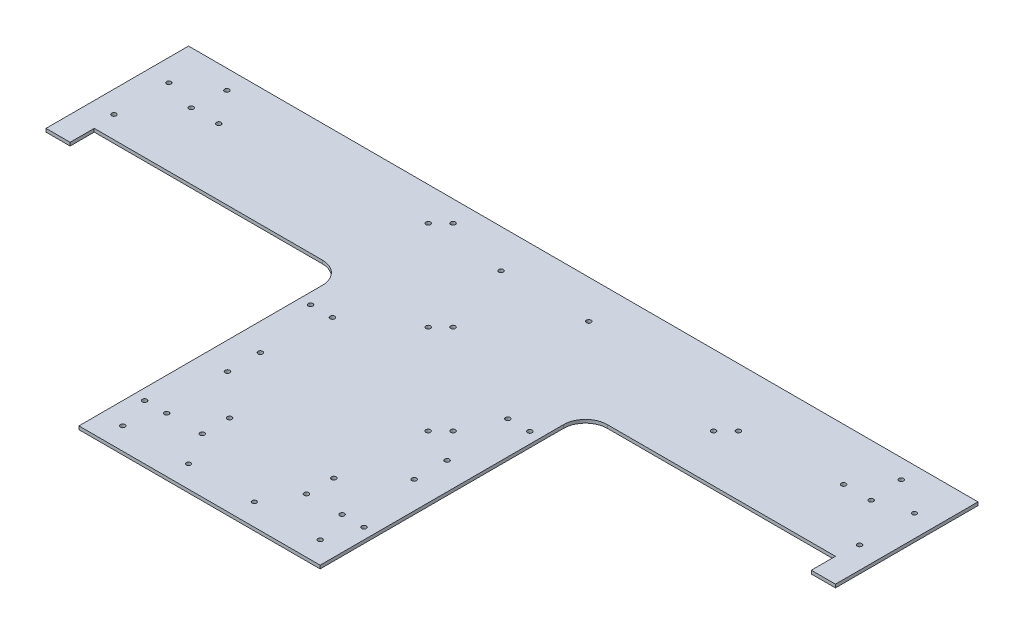
SolidWorks part; units mm, degrees
ref_plane "Front Plane" through (0, 0, 0) normal (0, 0, 1) x (1, 0, 0)
ref_plane "Top Plane" through (0, 0, 0) normal (0, 1, 0) x (1, 0, 0)
ref_plane "Right Plane" through (0, 0, 0) normal (1, 0, 0) x (0, 0, -1)
sketch "Sketch1" plane through (0, 0, 0) normal (0, 1, 0) x (1, 0, 0)
  line L0 (-110, 350) -> (-110, 108)
  line L1 (-110, 108) -> (-338, 108)
  line L2 (-338, 108) -> (-338, 130)
  line L3 (-338, 130) -> (-360, 130)
  line L4 (-360, 130) -> (-360, -130)
  line L5 (-360, 0) -> (1003.1457, 0) construction
  line L6 (0, 350) -> (0, -620.7989) construction
  line L7 (-338, -130) -> (-360, -130)
  line L8 (-338, -108) -> (-338, -130)
  line L9 (-110, -108) -> (-338, -108)
  line L10 (-110, 350) -> (110, 350)
  line L11 (-110, -350) -> (-110, -108)
  line L12 (-110, -350) -> (110, -350)
  line L13 (110, -350) -> (110, -108)
  line L14 (110, -108) -> (338, -108)
  line L15 (338, -108) -> (338, -130)
  line L16 (338, -130) -> (360, -130)
  line L17 (360, 130) -> (360, -130)
  line L18 (338, 130) -> (360, 130)
  line L19 (338, 108) -> (338, 130)
  line L20 (110, 108) -> (338, 108)
  line L21 (110, 350) -> (110, 108)
  point P17 (0, -350)
  dimension "D1" = 110
  dimension "D2" = 22
  dimension "D3" = 22
  dimension "D4" = 242
  dimension "D5" = 130
  dimension "D6" = 250
  dimension "D7" = 110
  dimension "D8" = 108
extrude "Boss-Extrude1" add sketch "Sketch1" along normal blind 3
sketch "Sketch2" plane through (0, 3, 0) normal (0, 1, 0) x (1, 0, 0)
  line L0 (360, -130) -> (360, 130) construction
  line L2 (338, 108) -> (110, 108) construction
  line L4 (0, 107.9437) -> (0, -458.275) construction
  line L5 (110, 108) -> (110, 350) construction
  line L6 (110, 350) -> (-110, 350) construction
  line L7 (-540.1841, 0) -> (-80.3508, 0) construction
  circle A0 centre (310, 47.5) radius 2.125
  circle A1 centre (285, 47.5) radius 2.125
  circle A2 centre (307.5, 17.5) radius 2.125
  circle A3 centre (307.5, -17.5) radius 2.125
  circle A4 centre (310, -47.5) radius 2.125
  circle A5 centre (285, -47.5) radius 2.125
  circle A6 centre (-285, -47.5) radius 2.125
  circle A7 centre (-310, -47.5) radius 2.125
  circle A8 centre (-307.5, -17.5) radius 2.125
  circle A9 centre (-307.5, 17.5) radius 2.125
  circle A10 centre (-285, 47.5) radius 2.125
  circle A11 centre (-310, 47.5) radius 2.125
  circle A13 centre (47.5, 300) radius 2.125
  circle A15 centre (47.5, 275) radius 2.125
  circle A16 centre (-47.5, 275) radius 2.125
  circle A17 centre (-47.5, 300) radius 2.125
  circle A18 centre (-47.5, -300) radius 2.125
  circle A19 centre (-47.5, -275) radius 2.125
  circle A20 centre (47.5, -275) radius 2.125
  circle A21 centre (47.5, -300) radius 2.125
  dimension "D1" = 4.25
  dimension "D2" = 4.25
  dimension "D3" = 4.25
  dimension "D4" = 4.25
  dimension "D5" = 4.25
  dimension "D6" = 4.25
  dimension "D15" = 4.25
  dimension "D16" = 4.25
  dimension "D7" = 50
  dimension "D8" = 25
  dimension "D9" = 95
  dimension "D10" = 35
  dimension "D11" = 60.5
  dimension "D12" = 90.5
  dimension "D13" = 52.5
  dimension "D14" = 110
  dimension "D17" = 50
  dimension "D18" = 25
  dimension "D19" = 62.5
  dimension "D20" = 108
extrude "Cut-Extrude1" cut sketch "Sketch2" against normal through all
sketch "Sketch3" plane through (0, 3, 0) normal (0, 1, 0) x (1, 0, 0)
  line L0 (360, -130) -> (360, 130) construction
  line L1 (338, 108) -> (110, 108) construction
  line L2 (-553.4456, 0) -> (-91.4299, 0) construction
  line L3 (0, 286.895) -> (0, -255.8046) construction
  line L4 (110, 108) -> (110, 350) construction
  line L5 (110, 350) -> (-110, 350) construction
  line L6 (-110, 350) -> (-110, 108) construction
  circle A0 centre (340, 38) radius 2
  circle A2 centre (340, -38) radius 2
  circle A3 centre (-340, -38) radius 2
  circle A4 centre (-340, 38) radius 2
  circle A5 centre (-30, 330) radius 2
  circle A7 centre (30, 330) radius 2
  circle A8 centre (30, -330) radius 2
  circle A9 centre (-30, -330) radius 2
  dimension "D1" = 4
  dimension "D6" = 4
  dimension "D7" = 80
  dimension "D2" = 20
  dimension "D3" = 70
  dimension "D4" = 108
  dimension "D5" = 110
  dimension "D8" = 20
extrude "Cut-Extrude2" cut sketch "Sketch3" against normal through all
sketch "Sketch5" plane through (0, 3, 0) normal (0, 1, 0) x (1, 0, 0)
  line L0 (110, 350) -> (-110, 350) construction
  line L1 (110, 108) -> (110, 350) construction
  line L2 (0, 224.365) -> (185.6725, 224.365) construction
  line L3 (90, 361.0488) -> (90, 126.2188) construction
  line L4 (0, 375.894) -> (0, 88.4107) construction
  line L5 (349.7475, 0) -> (-242.2654, 0) construction
  circle A0 centre (80, 300) radius 2.125
  circle A1 centre (80, 148.73) radius 2.125
  circle A2 centre (85.11, 239.365) radius 2.125
  circle A3 centre (85.11, 209.365) radius 2.125
  circle A4 centre (100, 148.73) radius 2.125
  circle A5 centre (100, 300) radius 2.125
  circle A6 centre (-100, 300) radius 2.125
  circle A7 centre (-100, 148.73) radius 2.125
  circle A8 centre (-85.11, 209.365) radius 2.125
  circle A9 centre (-85.11, 239.365) radius 2.125
  circle A10 centre (-80, 148.73) radius 2.125
  circle A11 centre (-80, 300) radius 2.125
  circle A12 centre (-80, -300) radius 2.125
  circle A13 centre (-80, -148.73) radius 2.125
  circle A14 centre (-85.11, -239.365) radius 2.125
  circle A15 centre (-85.11, -209.365) radius 2.125
  circle A16 centre (-100, -148.73) radius 2.125
  circle A17 centre (-100, -300) radius 2.125
  circle A18 centre (100, -300) radius 2.125
  circle A19 centre (100, -148.73) radius 2.125
  circle A20 centre (85.11, -209.365) radius 2.125
  circle A21 centre (85.11, -239.365) radius 2.125
  circle A22 centre (80, -148.73) radius 2.125
  circle A23 centre (80, -300) radius 2.125
  dimension "D1" = 4.25
  dimension "D2" = 4.25
  dimension "D6" = 4.25
  dimension "D7" = 4.25
  dimension "D3" = 151.27
  dimension "D4" = 50
  dimension "30" = 30
  dimension "D5" = 5.11
  dimension "D8" = 30
  dimension "D9" = 75.635
  dimension "D10" = 15
  dimension "D11" = 10
extrude "Cut-Extrude4" cut sketch "Sketch5" against normal blind 10
fillet "Fillet1" radius 20 4 edges at (110, 1.5, -108) (-110, 1.5, -108) (-110, 1.5, 108) (110, 1.5, 108)
sketch "Sketch6" plane through (0, 3, 0) normal (0, 1, 0) x (1, 0, 0)
  line L0 (-327.256, 327.256) -> (0, 0) construction
  line L1 (0, 429.479) -> (0, -412.5125) construction
  line L2 (-249.4214, 108) -> (110, -251.4214) construction
  line L3 (-226.7939, 108) -> (110, -228.7939) construction
  line L4 (327.256, 327.256) -> (0, 0) construction
  line L5 (-244.4559, 114.3482) -> (114.8318, -244.9395) construction
  line L6 (-130, 108) -> (-338, 108) construction
  line L7 (110, -350) -> (110, -128) construction
  circle A0 centre (53.3259, -194.7473) radius 2.125
  circle A1 centre (-192.7473, 51.3259) radius 2.125
  circle A2 centre (-28.6985, -112.7229) radius 2.125
  circle A3 centre (-110.7229, -30.6985) radius 2.125
  circle A4 centre (64.6396, -183.4335) radius 2.125
  circle A5 centre (-17.3848, -101.4092) radius 2.125
  circle A6 centre (-99.4092, -19.3848) radius 2.125
  circle A7 centre (-181.4335, 62.6396) radius 2.125
  circle A8 centre (-62.6396, 181.4335) radius 2.125
  circle A9 centre (19.3848, 99.4092) radius 2.125
  circle A10 centre (101.4092, 17.3848) radius 2.125
  circle A11 centre (183.4335, -64.6396) radius 2.125
  circle A12 centre (30.6985, 110.7229) radius 2.125
  circle A13 centre (112.7229, 28.6985) radius 2.125
  circle A14 centre (-51.3259, 192.7473) radius 2.125
  circle A15 centre (194.7473, -53.3259) radius 2.125
  point P23 (-69.7107, -71.7107)
  point P49 (71.7107, 69.7107)
  dimension "D3" = 4.25
  dimension "D5" = 4.25
  dimension "D8" = 4.25
  dimension "D10" = 4.25
  dimension "D1" = 45
  dimension "D2" = 100
  dimension "D4" = 16
  dimension "D6" = 348
  dimension "D7" = 174
  dimension "D9" = 116
  dimension "D11" = 116
  dimension "D12" = 8
extrude "Cut-Extrude5" cut sketch "Sketch6" against normal through all
sketch "Sketch7" plane through (0, 3, 0) normal (0, 1, 0) x (1, 0, 0)
  line L0 (0, 227.3539) -> (0, -244.3347) construction
  line L1 (-222.6371, 0) -> (245.907, 0) construction
  line L2 (360, -130) -> (360, 130) construction
  line L3 (338, 108) -> (130, 108) construction
  line L4 (110, 350) -> (-110, 350) construction
  line L5 (-110, 350) -> (-110, 128) construction
  circle A0 centre (340, 88) radius 2.1
  circle A1 centre (340, -88) radius 2.1
  circle A2 centre (-340, -88) radius 2.1
  circle A3 centre (-340, 88) radius 2.1
  circle A4 centre (-90, 330) radius 2.1
  circle A5 centre (90, 330) radius 2.1
  circle A6 centre (90, -330) radius 2.1
  circle A7 centre (-90, -330) radius 2.1
  dimension "D1" = 4.2
  dimension "D2" = 20
  dimension "D3" = 20
  dimension "D4" = 4.2
  dimension "D5" = 20
  dimension "D6" = 20
sketch "Sketch8" plane through (0, 3, 0) normal (0, 1, 0) x (1, 0, 0)
  line L0 (0, 227.3539) -> (0, -244.3347) construction
  line L1 (-222.6371, 0) -> (245.907, 0) construction
  line L2 (0, 89.3324) -> (0, -51.9249) construction
  line L3 (-114.1619, 0) -> (124.8762, 0) construction
  circle A0 centre (-40, 35) radius 2.1
  circle A1 centre (40, 35) radius 2.1
  circle A2 centre (40, -35) radius 2.1
  circle A3 centre (-40, -35) radius 2.1
  dimension "D1" = 4.2
  dimension "D2" = 40
  dimension "D3" = 35
extrude "Cut-Extrude6" cut sketch "Sketch8" against normal blind 10
extrude "Cut-Extrude7" cut sketch "Sketch7" against normal blind 10
sketch "Sketch9" plane through (0, 3, 0) normal (0, 1, 0) x (1, 0, 0)
  line L0 (-360, 130) -> (-360, -130) construction
  line L1 (-360, 0) -> (360, 0)
  line L2 (-360, 0) -> (-360, 350)
  line L3 (-360, 350) -> (360, 350)
  line L4 (360, 0) -> (360, 350)
  line L5 (110, 350) -> (-110, 350) construction
  line L6 (360, -130) -> (360, 130) construction
  dimension "D1" = 0
  dimension "D2" = 0
extrude "Cut-Extrude8" cut sketch "Sketch9" against normal blind 10
equation "\"M3\"= 4.25mm"
equation "\"D1@Sketch2\"=\"M3\""
equation "\"D2@Sketch2\"=\"M3\""
equation "\"D3@Sketch2\"=\"M3\""
equation "\"D4@Sketch2\"=\"M3\""
equation "\"D5@Sketch2\"=\"M3\""
equation "\"D6@Sketch2\"=\"M3\""
equation "\"D15@Sketch2\"=\"M3\""
equation "\"D16@Sketch2\"=\"M3\""
equation "\"D6@Sketch5\"=\"M3\""
equation "\"D7@Sketch5\"=\"M3\""
equation "\"D2@Sketch5\"=\"M3\""
equation "\"D10@Sketch6\"=\"M3\""
equation "\"D3@Sketch6\"=\"M3\""
equation "\"D8@Sketch6\"=\"M3\""
equation "\"D5@Sketch6\"=\"M3\""
